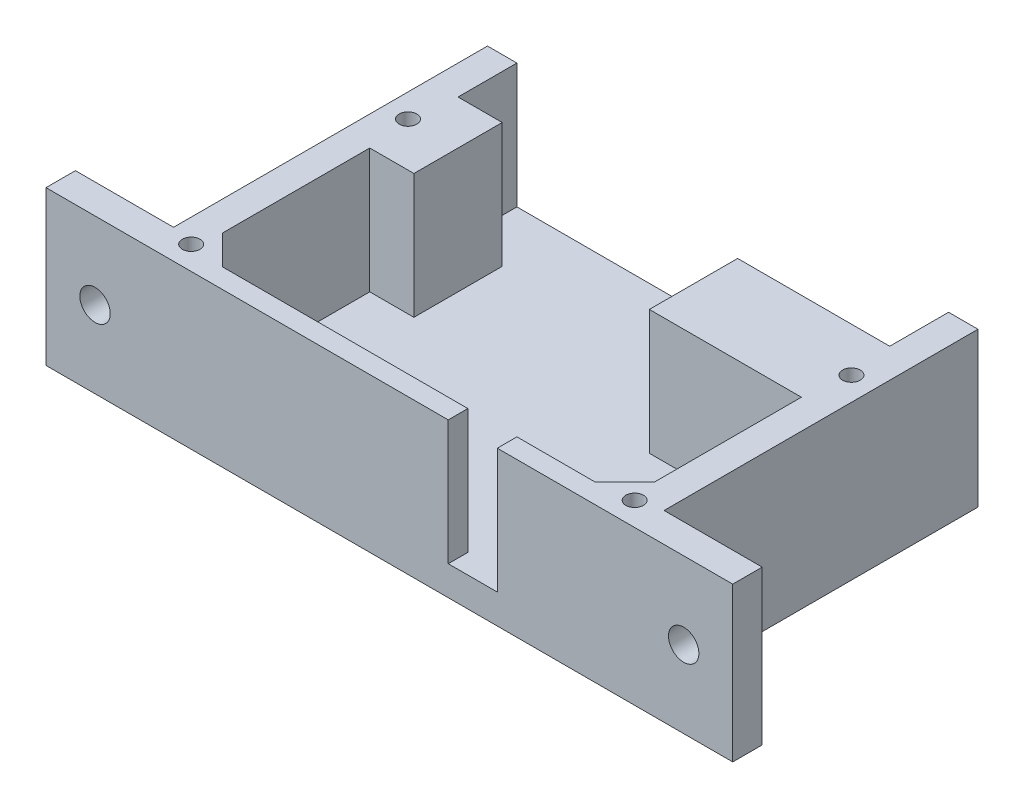
SolidWorks part; units mm, degrees
ref_plane "Front Plane" through (0, 0, 0) normal (0, 0, 1) x (1, 0, 0)
ref_plane "Top Plane" through (0, 0, 0) normal (0, 1, 0) x (1, 0, 0)
ref_plane "Right Plane" through (0, 0, 0) normal (1, 0, 0) x (0, 0, -1)
sketch "Sketch1" plane through (0, 0, 0) normal (0, 1, 0) x (1, 0, 0)
  line L1 (-25, 17.5) -> (25, 17.5)
  line L2 (-25, 17.5) -> (-25, -17.5)
  line L3 (-25, -17.5) -> (25, -17.5)
  line L4 (25, 17.5) -> (25, -17.5)
  line L5 (-25, 17.5) -> (25, -17.5) construction
  line L6 (-25, -17.5) -> (25, 17.5) construction
  point P0 (0, 0)
  dimension "D1" = 35
  dimension "D2" = 50
extrude "Boss-Extrude1" add sketch "Sketch1" along normal blind 3
sketch "Sketch2" plane through (0, 3, 0) normal (0, 1, 0) x (1, 0, 0)
  line L0 (-25, 17.5) -> (-25, -17.5) construction
  line L1 (-22, 11.5) -> (-17.5, 11.5)
  line L2 (-25, 11.5) -> (-25, 2.5)
  line L3 (-22, 2.5) -> (-17.5, 2.5)
  line L4 (-17.5, 11.5) -> (-17.5, 2.5)
  line L5 (25, -17.5) -> (25, 17.5) construction
  line L6 (22, 11.5) -> (6.5, 11.5)
  line L7 (25, 11.5) -> (25, 2.5)
  line L8 (22, 2.5) -> (6.5, 2.5)
  line L9 (6.5, 11.5) -> (6.5, 2.5)
  line L10 (25, 17.5) -> (-25, 17.5) construction
  line L11 (-25, -17.5) -> (25, -17.5) construction
  line L12 (-25, 17.5) -> (-22, 17.5)
  line L13 (-25, 17.5) -> (-25, -17.5)
  line L14 (-25, -17.5) -> (-22, -17.5)
  line L15 (-22, 17.5) -> (-22, 11.5)
  line L16 (-22, 2.5) -> (-22, -15.5)
  line L17 (25, 17.5) -> (22, 17.5)
  line L18 (25, 17.5) -> (25, -17.5)
  line L19 (25, -17.5) -> (22, -17.5)
  line L20 (22, 17.5) -> (22, 11.5)
  line L21 (22, 2.5) -> (22, -15.5)
  line L22 (11, -15.5) -> (22, -15.5)
  line L23 (-22, -17.5) -> (6, -17.5)
  line L25 (-22, -15.5) -> (6, -15.5)
  line L26 (6, -15.5) -> (6, -17.5)
  line L28 (11, -15.5) -> (11, -17.5)
  line L29 (11, -17.5) -> (22, -17.5)
  line M11 (25, -17.5) -> (25, 17.5)
  line M12 (25, 17.5) -> (-25, 17.5)
  line M13 (-25, 17.5) -> (-25, -17.5)
  line M14 (-25, -17.5) -> (25, -17.5)
  dimension "D1" = 9
  dimension "D2" = 9
  dimension "D3" = 6
  dimension "D4" = 6
  dimension "D5" = 24
  dimension "D6" = 18.5
  dimension "D7" = 3
  dimension "D8" = 3
  dimension "D9" = 2
  dimension "D10" = 5
extrude "Boss-Extrude2" add sketch "Sketch2" along normal blind 12.7 contours L22 L28 L20 L6 L9 L8 L21 M14 M11 M12 | L26 L25 L16 L3 L4 L1 L15 M12 M13 M14
chamfer "Chamfer1" distance 3 angle 45 2 edges at (22, 9.35, 15.5) (-22, 9.35, 15.5)
sketch "Sketch3" plane through (0, 15.7, 0) normal (0, 1, 0) x (1, 0, 0)
  line L0 (-25, 17.5) -> (-25, -17.5) construction
  line L1 (-25, -17.5) -> (6, -17.5) construction
  line L2 (25, -17.5) -> (25, 17.5) construction
  line L3 (11, -17.5) -> (25, -17.5) construction
  circle A0 centre (-22.6, -15.1) radius 0.9
  circle A1 centre (22.6, -15.1) radius 0.9
  circle A2 centre (22.6, 7) radius 0.9
  dimension "D1" = 1.8
  dimension "D2" = 2.4
  dimension "D3" = 2.4
  dimension "D4" = 1.8
  dimension "D5" = 2.4
  dimension "D6" = 2.4
  dimension "D7" = 1.8
  dimension "D8" = 2.4
extrude "Cut-Extrude1" cut sketch "Sketch3" against normal blind 8
sketch "Sketch4" plane through (0, 15.7, 0) normal (0, 1, 0) x (1, 0, 0)
  line L0 (-25, 17.5) -> (-25, -17.5) construction
  circle A0 centre (-22.6, 7) radius 0.9
  dimension "D1" = 1.8
  dimension "D2" = 2.4
extrude "Cut-Extrude2" cut sketch "Sketch4" against normal blind 8
sketch "Sketch5" plane through (0, 0, -11.5) normal (0, 0, -1) x (-1, 0, 0)
  line L0 (17.5, 15.7) -> (17.5, 3) construction
  line L1 (-6.5, 15.7) -> (-6.5, 3) construction
  circle A0 centre (20, 9.35) radius 0.9
  circle A1 centre (-9, 9.35) radius 0.9
  point P8 (-6.5, 9.35)
  dimension "D1" = 1.8
  dimension "D2" = 2.5
  dimension "D3" = 1.8
  dimension "D4" = 2.5
extrude "Cut-Extrude3" cut sketch "Sketch5" against normal blind 8
sketch "Sketch6" plane through (-25, 0, 0) normal (-1, 0, 0) x (0, 0, 1)
  line L0 (-17.5, 15.7) -> (17.5, 15.7) construction
  line L1 (17.5, 0) -> (14.5, 0)
  line L2 (17.5, 0) -> (17.5, 15.7)
  line L3 (17.5, 15.7) -> (14.5, 15.7)
  line L4 (14.5, 0) -> (14.5, 15.7)
  dimension "D1" = 3
extrude "Boss-Extrude3" add sketch "Sketch6" along normal blind 10
sketch "Sketch7" plane through (25, 0, 0) normal (1, 0, 0) x (0, 0, -1)
  line L0 (-17.5, 0) -> (17.5, 0) construction
  line L1 (-17.5, 15.7) -> (-14.5, 15.7)
  line L2 (-17.5, 15.7) -> (-17.5, 0)
  line L3 (-17.5, 0) -> (-14.5, 0)
  line L4 (-14.5, 15.7) -> (-14.5, 0)
  dimension "D1" = 3
extrude "Boss-Extrude4" add sketch "Sketch7" along normal blind 10
sketch "Sketch8" plane through (0, 0, 14.5) normal (0, 0, -1) x (-1, 0, 0)
  line L0 (35, 15.7) -> (35, 0) construction
  line L1 (-35, 0) -> (-35, 15.7) construction
  circle A0 centre (30, 7.85) radius 1.55
  circle A1 centre (-30, 7.85) radius 1.55
  dimension "D1" = 3.1
  dimension "D2" = 5
  dimension "D3" = 3.1
  dimension "D4" = 5
extrude "Cut-Extrude4" cut sketch "Sketch8" against normal blind 10
